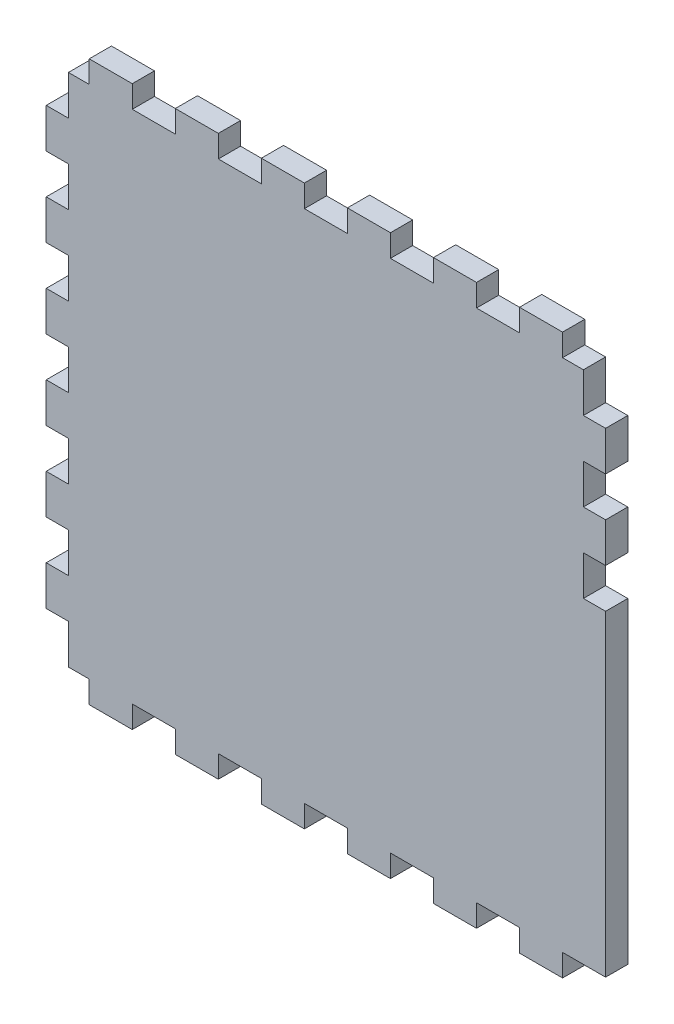
SolidWorks part; units mm, degrees
material "Acrylic (Medium-high impact)"
ref_plane "Front Plane" through (0, 0, 0) normal (0, 0, 1) x (1, 0, 0)
ref_plane "Top Plane" through (0, 0, 0) normal (0, 1, 0) x (1, 0, 0)
ref_plane "Right Plane" through (0, 0, 0) normal (1, 0, 0) x (0, 0, -1)
sketch "Sketch1" plane through (0, 0, 0) normal (0, 0, 1) x (1, 0, 0)
  line L1 (-40, -40) -> (40, -40)
  line L2 (-40, -40) -> (-40, 40)
  line L3 (-40, 40) -> (40, 40)
  line L4 (40, -40) -> (40, 40)
  line L5 (-40, -40) -> (40, 40) construction
  line L6 (-40, 40) -> (40, -40) construction
  point P0 (0, 0)
  dimension "D1" = 80
extrude "Boss-Extrude1" add sketch "Sketch1" along normal mid plane 3.175
sketch "Sketch3" plane through (0, 0, 1.5875) normal (0, 0, 1) x (1, 0, 0)
  line L0 (-36.825, 36.825) -> (-33.8462, 36.825)
  line L1 (-40, 40) -> (-40, -40) construction
  line L2 (-33.8462, 36.825) -> (-33.8462, 40)
  line L3 (40, 40) -> (-40, 40) construction
  line L4 (-33.8462, 40) -> (-27.6923, 40)
  line L5 (-27.6923, 40) -> (-27.6923, 36.825)
  line L6 (-27.6923, 36.825) -> (-21.5385, 36.825)
  line L7 (-21.5385, 36.825) -> (-21.5385, 40)
  line L8 (-21.5385, 40) -> (-15.3846, 40)
  line L9 (-15.3846, 40) -> (-15.3846, 36.825)
  line L10 (-15.3846, 36.825) -> (-9.2308, 36.825)
  line L11 (-9.2308, 36.825) -> (-9.2308, 40)
  line L12 (-9.2308, 40) -> (-3.0769, 40)
  line L13 (-3.0769, 40) -> (-3.0769, 36.825)
  line L14 (-3.0769, 36.825) -> (3.0769, 36.825)
  line L15 (3.0769, 36.825) -> (3.0769, 40)
  line L16 (3.0769, 40) -> (9.2308, 40)
  line L17 (9.2308, 40) -> (9.2308, 36.825)
  line L18 (9.2308, 36.825) -> (15.3846, 36.825)
  line L19 (15.3846, 36.825) -> (15.3846, 40)
  line L20 (15.3846, 40) -> (21.5385, 40)
  line L21 (21.5385, 40) -> (21.5385, 36.825)
  line L22 (21.5385, 36.825) -> (27.6923, 36.825)
  line L23 (27.6923, 36.825) -> (27.6923, 40)
  line L24 (27.6923, 40) -> (33.8462, 40)
  line L25 (33.8462, 40) -> (33.8462, 36.825)
  line L26 (33.8462, 40) -> (33.8462, 36.825) [skipped]
  line L27 (33.8462, 36.825) -> (36.825, 36.825)
  line L29 (-40, 0) -> (49960, 0) construction
  line L30 (33.8462, -36.825) -> (36.825, -36.825)
  line L31 (33.8462, -40) -> (33.8462, -36.825)
  line L32 (27.6923, -40) -> (33.8462, -40)
  line L33 (27.6923, -36.825) -> (27.6923, -40)
  line L34 (21.5385, -36.825) -> (27.6923, -36.825)
  line L35 (21.5385, -40) -> (21.5385, -36.825)
  line L36 (15.3846, -40) -> (21.5385, -40)
  line L37 (15.3846, -36.825) -> (15.3846, -40)
  line L38 (9.2308, -36.825) -> (15.3846, -36.825)
  line L39 (9.2308, -40) -> (9.2308, -36.825)
  line L40 (3.0769, -40) -> (9.2308, -40)
  line L41 (3.0769, -36.825) -> (3.0769, -40)
  line L42 (-3.0769, -36.825) -> (3.0769, -36.825)
  line L43 (-3.0769, -40) -> (-3.0769, -36.825)
  line L44 (-9.2308, -40) -> (-3.0769, -40)
  line L45 (-9.2308, -36.825) -> (-9.2308, -40)
  line L46 (-15.3846, -36.825) -> (-9.2308, -36.825)
  line L47 (-15.3846, -40) -> (-15.3846, -36.825)
  line L48 (-21.5385, -40) -> (-15.3846, -40)
  line L49 (-21.5385, -36.825) -> (-21.5385, -40)
  line L50 (-27.6923, -36.825) -> (-21.5385, -36.825)
  line L51 (-27.6923, -40) -> (-27.6923, -36.825)
  line L52 (-33.8462, -40) -> (-27.6923, -40)
  line L53 (-33.8462, -36.825) -> (-33.8462, -40)
  line L54 (-36.825, -36.825) -> (-33.8462, -36.825)
  line L57 (-36.825, 36.825) -> (-36.825, 31.1596)
  line L58 (-36.825, 31.1596) -> (-40, 31.1596)
  line L59 (-40, 31.1596) -> (-40, 25.4942)
  line L60 (-40, 25.4942) -> (-36.825, 25.4942)
  line L61 (-36.825, 25.4942) -> (-36.825, 19.8288)
  line L62 (-36.825, 19.8288) -> (-40, 19.8288)
  line L63 (-40, 19.8288) -> (-40, 14.1635)
  line L64 (-40, 14.1635) -> (-36.825, 14.1635)
  line L65 (-36.825, 14.1635) -> (-36.825, 8.4981)
  line L66 (-36.825, 8.4981) -> (-40, 8.4981)
  line L67 (-40, 8.4981) -> (-40, 2.8327)
  line L68 (-40, 2.8327) -> (-36.825, 2.8327)
  line L69 (-36.825, 2.8327) -> (-36.825, -2.8327)
  line L70 (-36.825, -2.8327) -> (-40, -2.8327)
  line L71 (-40, -2.8327) -> (-40, -8.4981)
  line L72 (-40, -8.4981) -> (-36.825, -8.4981)
  line L73 (-36.825, -8.4981) -> (-36.825, -14.1635)
  line L74 (-36.825, -14.1635) -> (-40, -14.1635)
  line L75 (-40, -14.1635) -> (-40, -19.8288)
  line L76 (-40, -19.8288) -> (-36.825, -19.8288)
  line L77 (-36.825, -19.8288) -> (-36.825, -25.4942)
  line L78 (-36.825, -25.4942) -> (-40, -25.4942)
  line L79 (-40, -25.4942) -> (-40, -31.1596)
  line L80 (-40, -31.1596) -> (-36.825, -31.1596)
  line L81 (-36.825, -31.1596) -> (-36.825, -36.825)
  line L82 (0, 0) -> (0, 50000) construction
  line L83 (36.825, 36.825) -> (36.825, 31.1596)
  line L84 (36.825, -31.1596) -> (36.825, -36.825)
  line L85 (40, -31.1596) -> (36.825, -31.1596)
  line L86 (40, -25.4942) -> (40, -31.1596)
  line L87 (36.825, -25.4942) -> (40, -25.4942)
  line L88 (36.825, -19.8288) -> (36.825, -25.4942)
  line L89 (40, -19.8288) -> (36.825, -19.8288)
  line L90 (40, -14.1635) -> (40, -19.8288)
  line L91 (36.825, -14.1635) -> (40, -14.1635)
  line L92 (36.825, -8.4981) -> (36.825, -14.1635)
  line L93 (40, -8.4981) -> (36.825, -8.4981)
  line L94 (40, -2.8327) -> (40, -8.4981)
  line L95 (36.825, -2.8327) -> (40, -2.8327)
  line L96 (36.825, 2.8327) -> (36.825, -2.8327)
  line L97 (40, 2.8327) -> (36.825, 2.8327)
  line L98 (40, 8.4981) -> (40, 2.8327)
  line L99 (36.825, 8.4981) -> (40, 8.4981)
  line L100 (36.825, 14.1635) -> (36.825, 8.4981)
  line L101 (40, 14.1635) -> (36.825, 14.1635)
  line L102 (40, 19.8288) -> (40, 14.1635)
  line L103 (36.825, 19.8288) -> (40, 19.8288)
  line L104 (36.825, 25.4942) -> (36.825, 19.8288)
  line L105 (40, 25.4942) -> (36.825, 25.4942)
  line L106 (40, 31.1596) -> (40, 25.4942)
  line L107 (36.825, 31.1596) -> (40, 31.1596)
  point P34 (-40, 0)
  point P74 (0, 40)
  dimension "D1" = 3.175
  dimension "D2" = 2.9788
  dimension "D3" = 2.9788
  dimension "D4" = 6
  dimension "D5" = 3.175
  dimension "D6" = 80
  dimension "D7" = 6
extrude "Cut-Extrude2" cut sketch "Sketch3" against normal through all flip side to cut
sketch "Sketch4" plane through (0, 0, 1.5875) normal (0, 0, 1) x (1, 0, 0)
  line L0 (40, 8.4981) -> (36.825, 8.4981) construction
  line L1 (36.825, -36.825) -> (40, -36.825)
  line L2 (36.825, -36.825) -> (36.825, 8.4981)
  line L3 (36.825, 8.4981) -> (40, 8.4981)
  line L4 (40, -36.825) -> (40, 8.4981)
  line L7 (40, -19.8288) -> (40, -14.1635) construction
  line L8 (36.825, -25.4942) -> (36.825, -19.8288) construction
  line L10 (33.8462, -36.825) -> (36.825, -36.825) construction
  point P12 (0, 0)
  point P13 (0, 0)
  point P14 (0, 0)
  point P15 (0, 0)
  point P16 (40, 14.1635)
  point P17 (0, 0)
extrude "Boss-Extrude2" add sketch "Sketch4" against normal up to surface (3.175 mm away) up to face at (0, 0, -1.5875)
